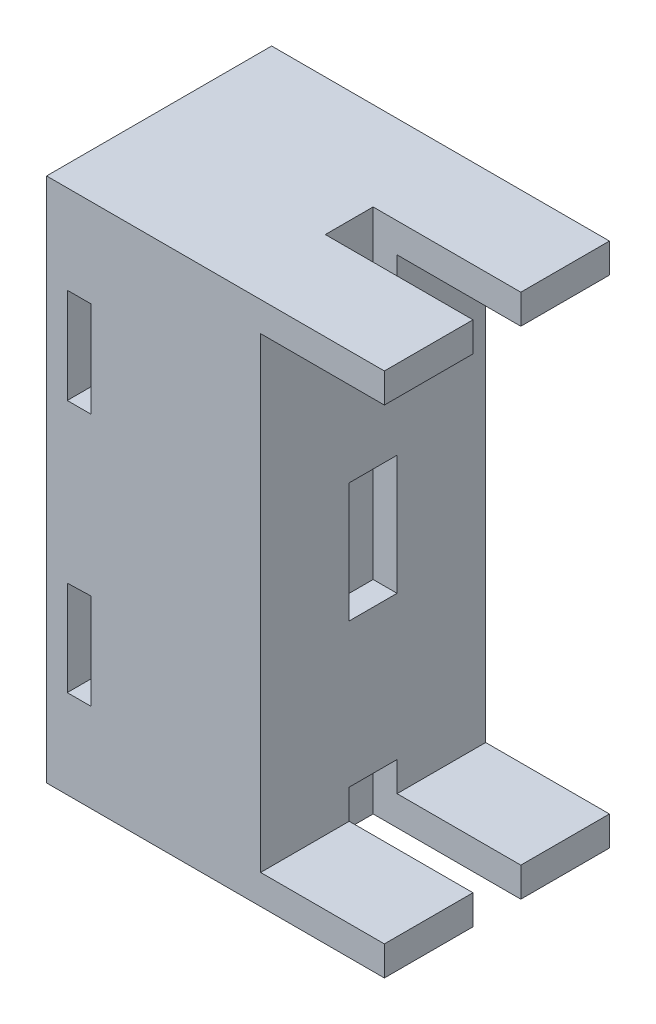
SolidWorks part; units mm, degrees
ref_plane "Front Plane" through (0, 0, 0) normal (0, 0, 1) x (1, 0, 0)
ref_plane "Top Plane" through (0, 0, 0) normal (0, 1, 0) x (1, 0, 0)
ref_plane "Right Plane" through (0, 0, 0) normal (1, 0, 0) x (0, 0, -1)
sketch "Sketch1" plane through (0, 0, 0) normal (0, 0, 1) x (1, 0, 0)
  line L0 (2.6031, 35.3123) -> (2.6031, 32.7723)
  line L5 (2.6031, 32.7723) -> (-8.0395, 32.7723)
  line L6 (-8.0395, 32.7723) -> (-8.0395, -7.3597)
  line L7 (-8.0395, -7.3597) -> (2.6031, -7.3597)
  line L8 (2.6031, -7.3597) -> (2.6031, -9.8997)
  line L9 (2.6031, -9.8997) -> (-10.0969, -9.8997)
  line L10 (-10.0969, -9.8997) -> (-10.0969, 35.3123)
  line L11 (-10.0969, 35.3123) -> (2.6031, 35.3123)
  dimension "D1" = 12.7
  dimension "D2" = 12.7
  dimension "D3" = 2.0574
  dimension "D4" = 40.132
  dimension "D5" = 2.54
  dimension "D6" = 2.54
extrude "Servo Clasper 2nd Half (Servo A)" add sketch "Sketch1" along normal blind 7.62
sketch "center encapsulator" plane through (0, 0, 0) normal (0, 0, 1) x (1, 0, 0)
  line L0 (-8.0395, -7.3597) -> (-8.0395, 32.7723) construction
  line L1 (-10.0969, 30.2958) -> (-8.0395, 30.2958)
  line L2 (-10.0969, 30.2958) -> (-10.0969, 17.8498)
  line L3 (-10.0969, 17.8498) -> (-8.0395, 17.8498)
  line L4 (-8.0395, 30.2958) -> (-8.0395, 17.8498)
  line L17 (-8.0395, 7.5628) -> (-10.0969, 7.5628)
  line L18 (-8.0395, 7.5628) -> (-8.0395, -4.8143)
  line L19 (-8.0395, -4.8143) -> (-10.0969, -4.8143)
  line L20 (-10.0969, 7.5628) -> (-10.0969, -4.8143)
  point P11 (-8.0395, 12.7063)
  dimension "D1" = 2.0574
  dimension "D2" = 2.0574
  dimension "D3" = 12.446
  dimension "D4" = 5.1435
  dimension "D5" = 5.1435
  dimension "D6" = 0
extrude "Vestigial but nice" add sketch "center encapsulator" along normal blind 4.1148 from surface at 7.62 starting at face at (-3.2325, 12.7063, 7.62)
sketch "Sketch7" plane through (0, 0, 0) normal (0, 0, 1) x (1, 0, 0)
  line L0 (2.6031, 35.3123) -> (2.6031, 32.7723)
  line L5 (2.6031, 32.7723) -> (-8.0395, 32.7723)
  line L6 (-8.0395, 32.7723) -> (-8.0395, -7.3597)
  line L7 (-8.0395, -7.3597) -> (2.6031, -7.3597)
  line L8 (2.6031, -7.3597) -> (2.6031, -9.8997)
  line L9 (2.6031, -9.8997) -> (-10.0969, -9.8997)
  line L10 (-10.0969, -9.8997) -> (-10.0969, 35.3123)
  line L11 (-10.0969, 35.3123) -> (2.6031, 35.3123)
  dimension "D1" = 12.7
  dimension "D2" = 12.7
  dimension "D3" = 2.0574
  dimension "D4" = 40.132
  dimension "D5" = 2.54
  dimension "D6" = 2.54
extrude "Servo Clasper 2nd Half (Other Servo)" add sketch "Sketch7" along normal blind 7.62 from surface at 11.7348 starting at face at (-9.0682, 24.0728, 11.7348)
sketch "Sketch8" plane through (0, 0, 0) normal (0, 0, 1) x (1, 0, 0)
  line L0 (-10.0969, 31.5023) -> (-8.0395, 31.5023)
  line L1 (-10.0969, 31.5023) -> (-10.0969, 23.8823)
  line L2 (-10.0969, 23.8823) -> (-8.0395, 23.8823)
  line L3 (-8.0395, 31.5023) -> (-8.0395, 23.8823)
  line L4 (-10.0969, 35.3123) -> (-10.0969, -9.8997) construction
  line L5 (2.6031, 35.3123) -> (-10.0969, 35.3123) construction
  point P6 (-9.0682, 31.5023)
  dimension "D1" = 0
  dimension "D2" = 3.81
  dimension "D3" = 7.62
sketch "Sketch10" plane through (0, 0, 0) normal (0, 0, 1) x (1, 0, 0)
  line L0 (2.6031, 35.5663) -> (2.6031, 33.0263)
  line L5 (2.6031, 33.0263) -> (-8.0395, 33.0263)
  line L6 (-8.0395, 33.0263) -> (-8.0395, -7.3597)
  line L7 (-8.0395, -7.3597) -> (2.6031, -7.3597)
  line L8 (2.6031, -7.3597) -> (2.6031, -9.8997)
  line L9 (2.6031, -9.8997) -> (-10.0969, -9.8997)
  line L10 (-10.0969, -9.8997) -> (-10.0969, 35.5663)
  line L11 (-10.0969, 35.5663) -> (2.6031, 35.5663)
  dimension "D1" = 12.7
  dimension "D2" = 12.7
  dimension "D3" = 2.0574
  dimension "D4" = 40.386
  dimension "D5" = 2.54
  dimension "D6" = 2.54
sketch "Sketch12" plane through (-10.0969, 0, 0) normal (-1, 0, 0) x (0, 0, 1)
  line L1 (0, 35.3123) -> (19.3548, 35.3123)
  line L2 (0, 35.3123) -> (0, -9.8997)
  line L3 (0, -9.8997) -> (19.3548, -9.8997)
  line L4 (19.3548, 35.3123) -> (19.3548, -9.8997)
extrude "Servo Holder Extrude" add sketch "Sketch12" along normal blind 16.35
sketch "Sketch13" plane through (0, 35.3123, 0) normal (0, 1, 0) x (1, 0, 0)
  line L0 (-10.0969, 0) -> (-8.0395, 0) construction
  line L5 (-19.2017, -7.6614) -> (-17.9137, -7.6614)
  line L6 (-19.2017, -7.6614) -> (-19.2017, -15.5354)
  line L7 (-19.2017, -15.5354) -> (-17.9137, -15.5354)
  line L8 (-18.4124, 0) -> (-15.3644, 0)
  line L9 (-18.4124, 0) -> (-18.4124, -33.528)
  line L10 (-18.4124, -33.528) -> (-15.3644, -33.528)
  line L11 (-15.3644, 0) -> (-15.3644, -33.528)
  line L12 (-17.9137, -7.6614) -> (-17.9137, -15.5354)
  dimension "D1" = 3.048
  dimension "D2" = 33.528
  dimension "D3" = 1.2879
  dimension "D4" = 7.874
  dimension "D5" = 0
sketch "Sketch14" plane through (-26.4469, 0, 0) normal (-1, 0, 0) x (0, 0, 1)
  line L0 (7.2961, 29.4703) -> (12.0586, 29.4703)
  line L2 (5.1689, 14.6875) -> (5.1689, 10.7251)
  line L6 (12.0586, 29.4703) -> (14.1859, 14.6875)
  line L7 (7.2961, -4.0577) -> (12.0586, -4.0577)
  line L8 (14.1859, 10.7251) -> (14.1859, 14.6875)
  line L9 (7.2961, 29.4703) -> (5.1689, 14.6875)
  line L10 (5.1689, 10.7251) -> (7.2961, -4.0577)
  line L11 (12.0586, -4.0577) -> (14.1859, 10.7251)
  line L12 (7.6614, 35.3123) -> (15.5354, 35.3123) construction
  dimension "D2" = 9.017
  dimension "D3" = 5.842
  dimension "D4" = 171.811
  dimension "D5" = 33.528
  dimension "D7" = 4.7625
  dimension "D8" = 3.9624
  dimension "D9" = 171.811
  dimension "D10" = 171.811
  dimension "D11" = 171.811
  dimension "D12" = 3.9624
extrude "Servo B Cut" cut sketch "Sketch14" against normal blind 7.62
sketch "Sketch18" plane through (0, 0, 0) normal (0, 0, -1) x (-1, 0, 0)
  line L1 (26.4469, 35.3123) -> (26.4469, -9.8997) construction
  line L5 (24.6689, 27.6923) -> (22.6369, 27.6923)
  line L6 (22.6369, 27.6923) -> (22.6369, 19.4765)
  line L7 (22.6369, 19.4765) -> (24.6689, 19.4765)
  line L8 (24.6689, 19.4765) -> (24.6689, 27.6923)
  line L11 (26.4469, -9.8997) -> (-2.6031, -9.8997) construction
  line L12 (-2.6031, 35.3123) -> (26.4469, 35.3123) construction
  line L13 (24.6689, 5.8746) -> (22.6369, 5.9361)
  line L14 (22.6369, 5.9361) -> (22.6369, -2.2797)
  line L15 (22.6369, -2.2797) -> (24.6689, -2.2797)
  line L16 (24.6689, -2.2797) -> (24.6689, 5.8746)
  dimension "D1" = 1.778
  dimension "D2" = 2.032
  dimension "D3" = 8.2158
  dimension "D4" = 7.62
  dimension "D5" = 8.2158
  dimension "D6" = 1.778
  dimension "D7" = 7.62
  dimension "D8" = 2.032
extrude "Servo B Securer Cut" cut sketch "Sketch18" against normal through all both
